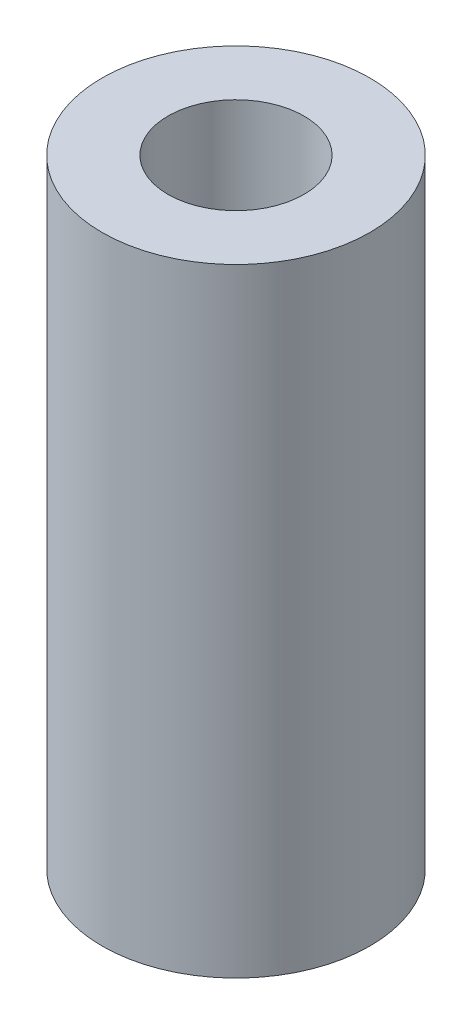
SolidWorks part; units mm, degrees
ref_plane "Front Plane" through (0, 0, 0) normal (0, 0, 1) x (1, 0, 0)
ref_plane "Top Plane" through (0, 0, 0) normal (0, 1, 0) x (1, 0, 0)
ref_plane "Right Plane" through (0, 0, 0) normal (1, 0, 0) x (0, 0, -1)
sketch "Sketch1" plane through (0, 0, 0) normal (0, 1, 0) x (1, 0, 0)
  circle A0 centre (0, 0) radius 1.65
  circle A1 centre (0, 0) radius 3.25
  dimension "D1" = 3.3
  dimension "D2" = 6.5
extrude "Boss-Extrude1" add sketch "Sketch1" along normal blind 15
